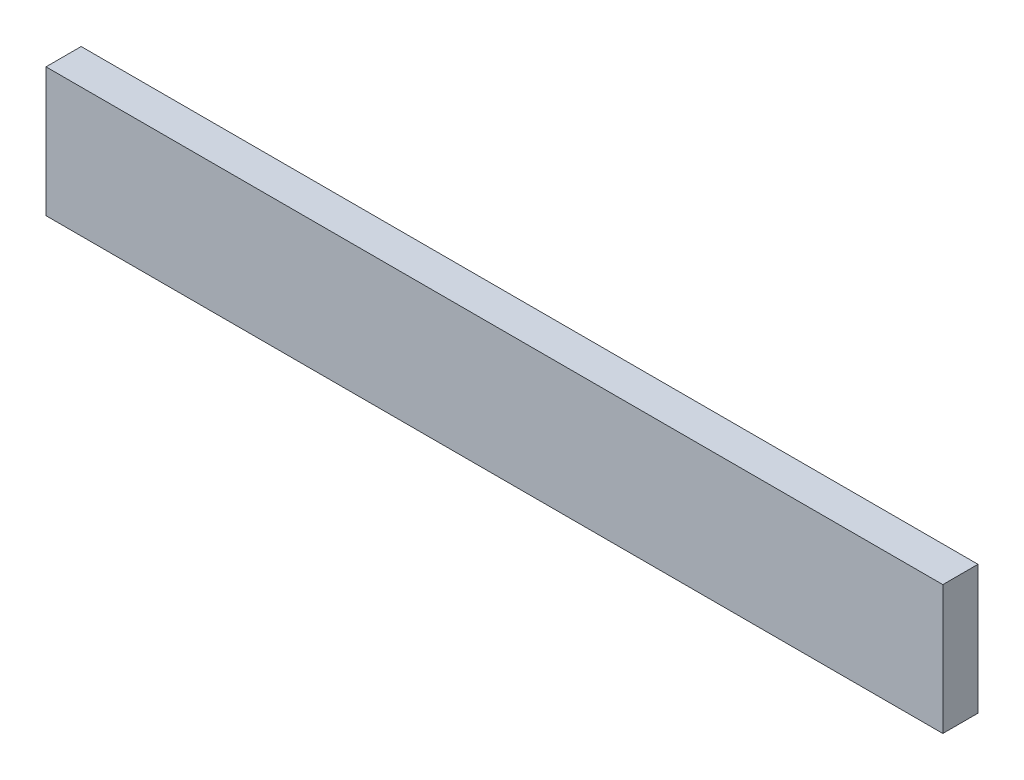
SolidWorks part; units mm, degrees
ref_plane "前视基准面" through (0, 0, 0) normal (0, 0, 1) x (1, 0, 0)
ref_plane "上视基准面" through (0, 0, 0) normal (0, 1, 0) x (1, 0, 0)
ref_plane "右视基准面" through (0, 0, 0) normal (1, 0, 0) x (0, 0, -1)
other "Configuration Table"
sketch "草图1" plane through (0, 0, 0) normal (0, 0, 1) x (1, 0, 0)
  line L0 (0, 0) -> (153, 0)
  line L1 (153, 0) -> (153, 22)
  line L2 (153, 22) -> (0, 22)
  line L3 (0, 22) -> (0, 0)
  dimension "width" = 153
  dimension "height" = 22
extrude "Seat_to_frame" add sketch "草图1" along normal blind 6
